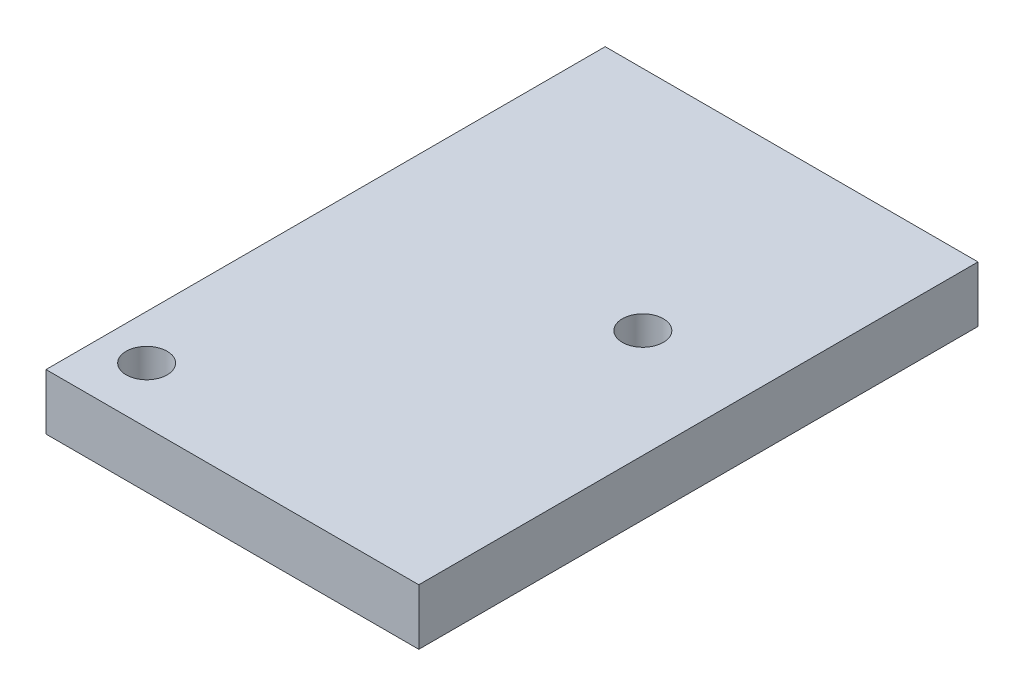
SolidWorks part; units mm, degrees
ref_plane "Front Plane" through (0, 0, 0) normal (0, 0, 1) x (1, 0, 0)
ref_plane "Top Plane" through (0, 0, 0) normal (0, 1, 0) x (1, 0, 0)
ref_plane "Right Plane" through (0, 0, 0) normal (1, 0, 0) x (0, 0, -1)
ref_plane "Plane1"
sketch "Sketch1" plane through (0, 0, 0) normal (0, 1, 0) x (-1, 0, 0)
  line L0 (0, 0) -> (1000, 0)
  line L1 (1000, 0) -> (1000, 1500)
  line L2 (1000, 1500) -> (0, 1500)
  line L3 (0, 1500) -> (0, 0)
  dimension "D1" = 1000
  dimension "D2" = 1500
extrude "base" add sketch "Sketch1" along normal blind 150
sketch "Sketch2" plane through (0, 150, 0) normal (0, 1, 0) x (-1, 0, 0)
  circle A0 centre (290, 609) radius 55
  dimension "D1" = 110
extrude "air" cut sketch "Sketch2" against normal through all
hole_wizard "air2" positions "Sketch4" profile "Sketch3" legacy end condition through all
sketch "Sketch4" plane through (0, 150, 0) normal (0, 1, 0) x (1, 0, 0)
  point P1 (-880, -1350)
sketch "Sketch3" plane through (-880, 150, 1350) normal (1, 0, 0) x (0, 0, 1)
  line L0 (0, 0) -> (0, 150)
  line L1 (0, 150) -> (55, 150)
  line L2 (55, 150) -> (55, 0)
  line L3 (55, 0) -> (0, 0)
  line L4 (0, 110) -> (0, -10) construction
  dimension "Diameter" = 110
  dimension "Depth" = 150
